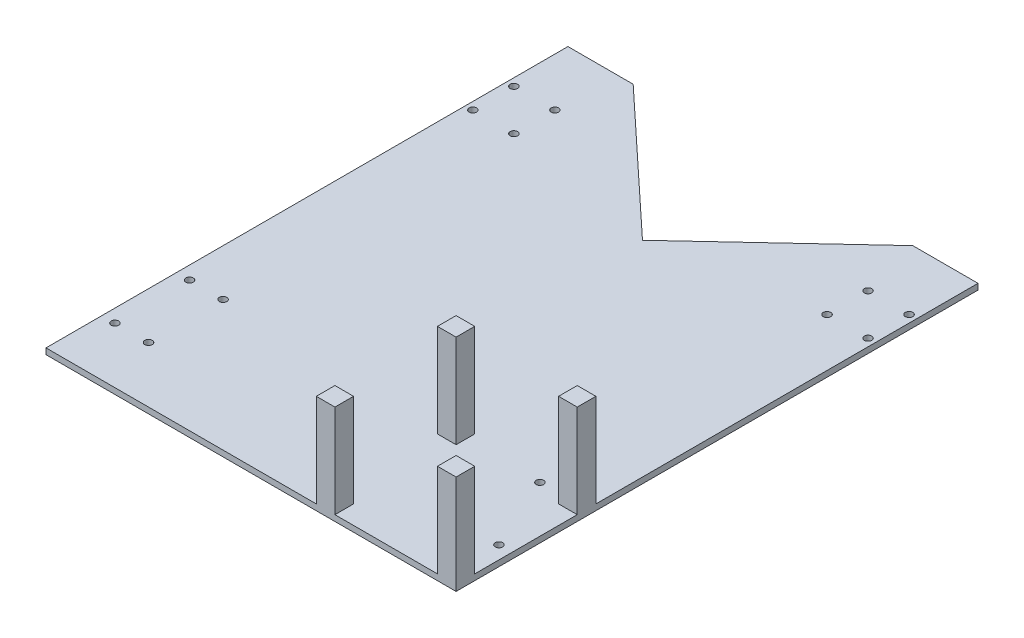
SolidWorks part; units mm, degrees
material "Pine"
ref_plane "Front Plane" through (0, 0, 0) normal (0, 0, 1) x (1, 0, 0)
ref_plane "Top Plane" through (0, 0, 0) normal (0, 1, 0) x (1, 0, 0)
ref_plane "Right Plane" through (0, 0, 0) normal (1, 0, 0) x (0, 0, -1)
sketch "Sketch3" plane through (0, 0, 0) normal (0, 1, 0) x (1, 0, 0)
  line L1 (-110, -140) -> (110, -140)
  line L2 (-110, -140) -> (-110, 140)
  line L3 (-110, 140) -> (110, 140)
  line L4 (110, -140) -> (110, 140)
  line L5 (-110, -140) -> (110, 140) construction
  line L6 (-110, 140) -> (110, -140) construction
  point P0 (0, 0)
  dimension "D1" = 220
  dimension "D2" = 280
extrude "Boss-Extrude1" add sketch "Sketch3" along normal blind 3.175
sketch "Sketch4" plane through (0, 3.175, 0) normal (0, 1, 0) x (1, 0, 0)
  line L0 (110, -140) -> (110, 140) construction
  line L1 (110, -140) -> (100, -140)
  line L2 (110, -140) -> (110, -130)
  line L3 (110, -65) -> (100, -65)
  line L4 (35, -140) -> (35, -130)
  line L5 (-110, -140) -> (110, -140) construction
  line L6 (45, -140) -> (45, -130)
  line L7 (100, -65) -> (100, -75)
  line L8 (45, -65) -> (35, -65)
  line L9 (45, -140) -> (35, -140)
  line L10 (35, -130) -> (45, -130)
  line L11 (35, -75) -> (45, -75)
  line L12 (100, -75) -> (110, -75)
  line L13 (100, -130) -> (110, -130)
  line L14 (35, -75) -> (35, -65)
  line L15 (45, -75) -> (45, -65)
  line L16 (100, -130) -> (100, -140)
  line L17 (110, -75) -> (110, -65)
  point P20 (105, -130)
  dimension "D1" = 0
  dimension "D2" = 0
  dimension "D3" = 75
  dimension "D4" = 75
  dimension "D5" = 10
  dimension "D6" = 10
  dimension "D7" = 10
  dimension "D8" = 10
  dimension "D9" = 10
extrude "Boss-Extrude2" add sketch "Sketch4" along normal blind 50
sketch "Sketch7" plane through (0, 0, 0) normal (0, -1, 0) x (1, 0, 0)
  line L0 (110, 140) -> (110, -140) construction
  line L1 (-110, 140) -> (110, 140) construction
  line L2 (110, -140) -> (-110, -140) construction
  line L3 (0, 0) -> (0, -140) construction
  line L4 (-103, 70) -> (103, 70) construction
  line L5 (-103, 110) -> (103, 110) construction
  line L6 (-110, -140) -> (-110, 140) construction
  line L7 (-85, 110) -> (-85, 140) construction
  line L8 (-85, 110) -> (-85, 70) construction
  line L9 (-103, 110) -> (-103, 70) construction
  line L10 (103, 70) -> (103, 110) construction
  line L11 (85, 110) -> (85, 70) construction
  circle A8 centre (-103, 70) radius 2
  circle A9 centre (-103, 110) radius 2
  circle A10 centre (-85, 110) radius 2
  circle A11 centre (-85, 70) radius 2
  circle A12 centre (85, 110) radius 2
  circle A13 centre (103, 110) radius 2
  circle A14 centre (103, 70) radius 2
  circle A15 centre (85, 70) radius 2
  circle A16 centre (106, -107) radius 2
  circle A17 centre (84, -85) radius 2
  circle A18 centre (106, -85) radius 2
  circle A19 centre (84, -107) radius 2
  circle A20 centre (-84, -107) radius 2
  circle A21 centre (-106, -107) radius 2
  circle A22 centre (-106, -85) radius 2
  circle A23 centre (-84, -85) radius 2
  dimension "D12" = 40
  dimension "D4" = 7
  dimension "D3" = 18
  dimension "D5" = 40
  dimension "D6" = 40
  dimension "D7" = 18
  dimension "D8" = 4
  dimension "D9" = 33
  dimension "D10" = 22
  dimension "D11" = 22
  dimension "D13" = 40
  dimension "D16" = 7
  dimension "D27" = 30
extrude "Cut-Extrude2" cut sketch "Sketch7" against normal blind 10
sketch "Sketch8" plane through (0, 3.175, 0) normal (0, 1, 0) x (1, 0, 0)
  line L0 (-110, -140) -> (35, -140) construction
  line L1 (-110, 140) -> (-110, -140) construction
  line L2 (110, -65) -> (110, 140) construction
  circle A0 centre (-45, -35) radius 4
  circle A1 centre (-25, -35) radius 4
  circle A5 centre (-45, 40) radius 4
  circle A6 centre (-25, 40) radius 4
  circle A7 centre (55, 2.5) radius 4
  circle A8 centre (75, 2.5) radius 4
  dimension "D1" = 8
  dimension "D2" = 8
  dimension "D4" = 8
  dimension "D5" = 8
  dimension "D7" = 8
  dimension "D8" = 8
  dimension "D3" = 20
  dimension "D6" = 20
  dimension "D9" = 20
  dimension "D10" = 105
  dimension "D11" = 65
  dimension "D12" = 65
  dimension "D13" = 75
  dimension "D14" = 37.5
  dimension "D15" = 35
extrude "Cut-Extrude3" [suppressed] cut sketch "Sketch8" against normal blind 10
sketch "Sketch9" plane through (0, 3.175, 0) normal (0, 1, 0) x (1, 0, 0)
  line L5 (50, 98.4245) -> (110, 98.4245) construction
  line L6 (110, -65) -> (110, 140) construction
  line L7 (-50, 98.4245) -> (-110, 98.4245) construction
  line L8 (-110, 140) -> (-110, -140) construction
  line L13 (-110, 70) -> (110, 70) construction
  line L14 (0, 70) -> (75, 140)
  line L15 (110, 140) -> (-110, 140) construction
  line L16 (75, 140) -> (-75, 140)
  line L17 (-75, 140) -> (0, 70)
  line L18 (0, 70) -> (0, 140) construction
  dimension "D1" = 150
  dimension "D2" = 35
  dimension "D3" = 70
extrude "Cut-Extrude4" cut sketch "Sketch9" against normal blind 10
